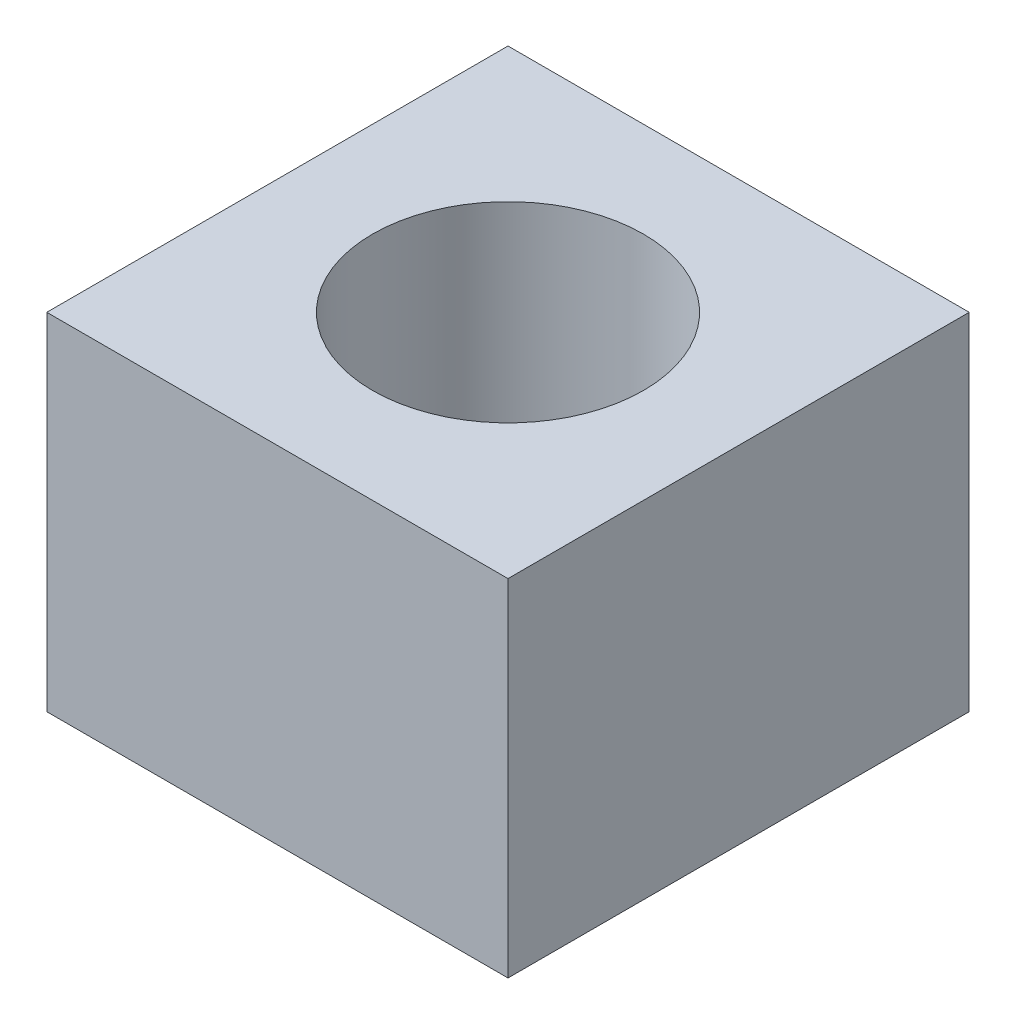
SolidWorks part; units mm, degrees
ref_plane "Front Plane" through (0, 0, 0) normal (0, 0, 1) x (1, 0, 0)
ref_plane "Top Plane" through (0, 0, 0) normal (0, 1, 0) x (1, 0, 0)
ref_plane "Right Plane" through (0, 0, 0) normal (1, 0, 0) x (0, 0, -1)
sketch "Sketch1" plane through (0, 0, 0) normal (0, 1, 0) x (1, 0, 0)
  line L1 (-40, -40) -> (40, -40)
  line L2 (-40, -40) -> (-40, 40)
  line L3 (-40, 40) -> (40, 40)
  line L4 (40, -40) -> (40, 40)
  line L5 (-40, -40) -> (40, 40) construction
  line L6 (-40, 40) -> (40, -40) construction
  point P0 (0, 0)
extrude "Boss-Extrude1" add sketch "Sketch1" along normal blind 60
sketch "Sketch2" plane through (0, 60, 0) normal (0, 1, 0) x (1, 0, 0)
  circle A0 centre (0, 0) radius 23.5
  dimension "D1" = 47
extrude "Cut-Extrude1" cut sketch "Sketch2" against normal blind 44.2
